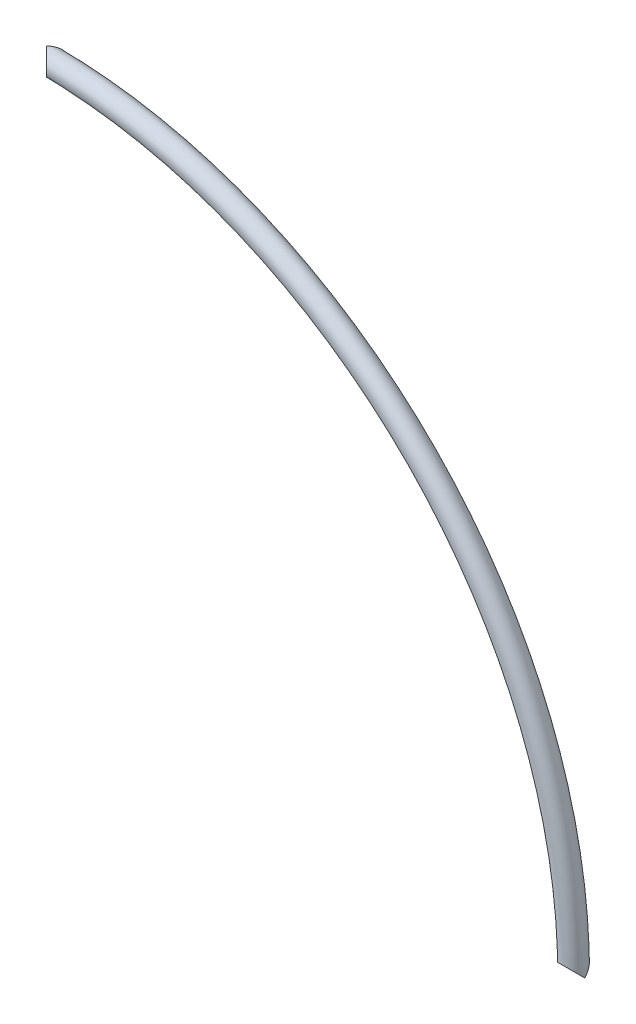
SolidWorks part; units mm, degrees
material "PVC Rigid"
ref_plane "Front Plane" through (0, 0, 0) normal (0, 0, 1) x (1, 0, 0)
ref_plane "Top Plane" through (0, 0, 0) normal (0, 1, 0) x (1, 0, 0)
ref_plane "Right Plane" through (0, 0, 0) normal (1, 0, 0) x (0, 0, -1)
sketch "Sketch1" plane through (0, 0, 0) normal (0, 0, 1) x (1, 0, 0)
  line L0 (0, 500) -> (0, 0) construction
  line L1 (0, 0) -> (500, 0) construction
  line L2 (0, 0) -> (353.5534, 353.5534) construction
  arc A0 (0, 500) -> (500, 0) centre (0, 0) cw
  dimension "D1" = 500
  dimension "D2" = 45
sketch "Sketch2" plane through (0, 0, 0) normal (0, 1, 0) x (1, 0, 0)
  line L0 (0, 0) -> (500, 0) construction
  circle A0 centre (500, 0) radius 7.8994
  circle A1 centre (500, 0) radius 10.668
  dimension "D1" = 15.7988
  dimension "D2" = 2.7686
sweep "Sweep1" add profiles "Sketch2" path "Sketch1"
sketch "Sketch3" plane through (0, 0, 0) normal (0, 1, 0) x (1, 0, 0)
  line L0 (0, 0) -> (10.668, 10.668)
  line L1 (500, 10.668) -> (0, 10.668) construction
  line L2 (10.668, 10.668) -> (-11.5753, 10.668)
  line L3 (-11.5753, 10.668) -> (-11.5753, -10.668)
  line L4 (-11.5753, -10.668) -> (10.668, -10.668)
  line L5 (0, -10.668) -> (500, -10.668) construction
  line L6 (10.668, -10.668) -> (0, 0)
  line L7 (0, -10.668) -> (500, -10.668) construction
  line L9 (10.668, -10.668) -> (10.668, 10.668) construction
  dimension "D1" = 90
sketch "Sketch4" plane through (0, 0, 0) normal (1, 0, 0) x (0, 0, -1)
  line L0 (0, 0) -> (-10.668, 10.668)
  line L1 (-10.668, 500) -> (-10.668, 0) construction
  line L2 (-10.668, 10.668) -> (-10.668, -2.0461)
  line L3 (-10.668, -2.0461) -> (10.668, -2.0461)
  line L4 (10.668, -2.0461) -> (10.668, 10.668)
  line L5 (10.668, 10.668) -> (0, 0)
  line L6 (-10.668, 10.668) -> (10.668, 10.668) construction
  line L8 (-10.668, 0) -> (0, 0) construction
  line L9 (-10.668, 0) -> (10.668, 0) construction
  line L10 (0, 0) -> (10.668, 0) construction
  dimension "D1" = 90
extrude "Cut-Extrude2" cut sketch "Sketch4" along normal through all
extrude "Cut-Extrude4" cut sketch "Sketch3" along normal up to next and the other way through all
